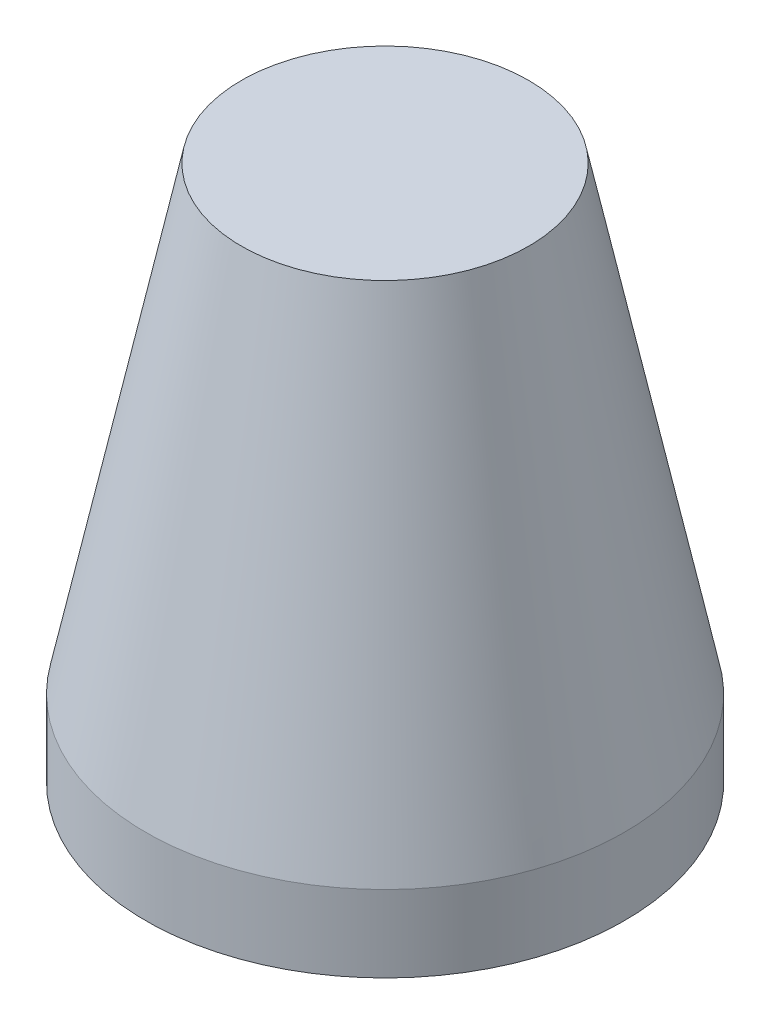
SolidWorks part; units mm, degrees
ref_plane "Front Plane" through (0, 0, 0) normal (0, 0, 1) x (1, 0, 0)
ref_plane "Top Plane" through (0, 0, 0) normal (0, 1, 0) x (1, 0, 0)
ref_plane "Right Plane" through (0, 0, 0) normal (1, 0, 0) x (0, 0, -1)
sketch "草图1" plane through (0, 0, 0) normal (0, 0, 1) x (1, 0, 0)
  line L0 (0, 0) -> (0, 40) construction
  line L1 (0, 40) -> (-15, 40)
  line L2 (-15, 40) -> (-25, -8)
  line L3 (-25, -8) -> (-25, -16)
  line L4 (-25, -16) -> (0, -16)
  line L5 (0, -16) -> (0, 40)
  dimension "D1" = 8
  dimension "D2" = 25
  dimension "D3" = 15
  dimension "D4" = 56
revolve "旋转1" add sketch "草图1" angle 360 about L0
